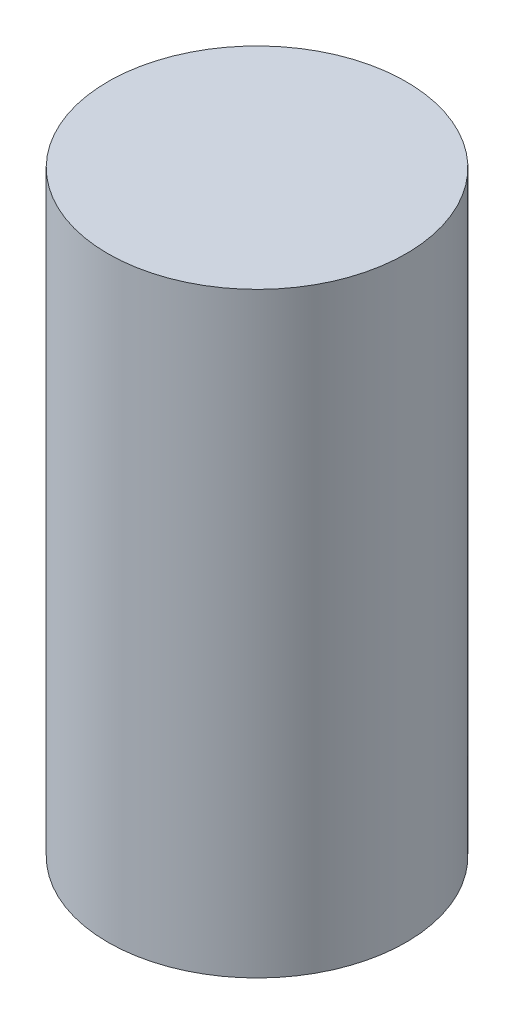
SolidWorks part; units mm, degrees
ref_plane "Front Plane" through (0, 0, 0) normal (0, 0, 1) x (1, 0, 0)
ref_plane "Top Plane" through (0, 0, 0) normal (0, 1, 0) x (1, 0, 0)
ref_plane "Right Plane" through (0, 0, 0) normal (1, 0, 0) x (0, 0, -1)
sketch "Sketch1" plane through (0, 0, 0) normal (0, 1, 0) x (1, 0, 0)
  circle A0 centre (0, 0) radius 1.5
  dimension "D1" = 3
extrude "Boss-Extrude1" add sketch "Sketch1" along normal blind 6
